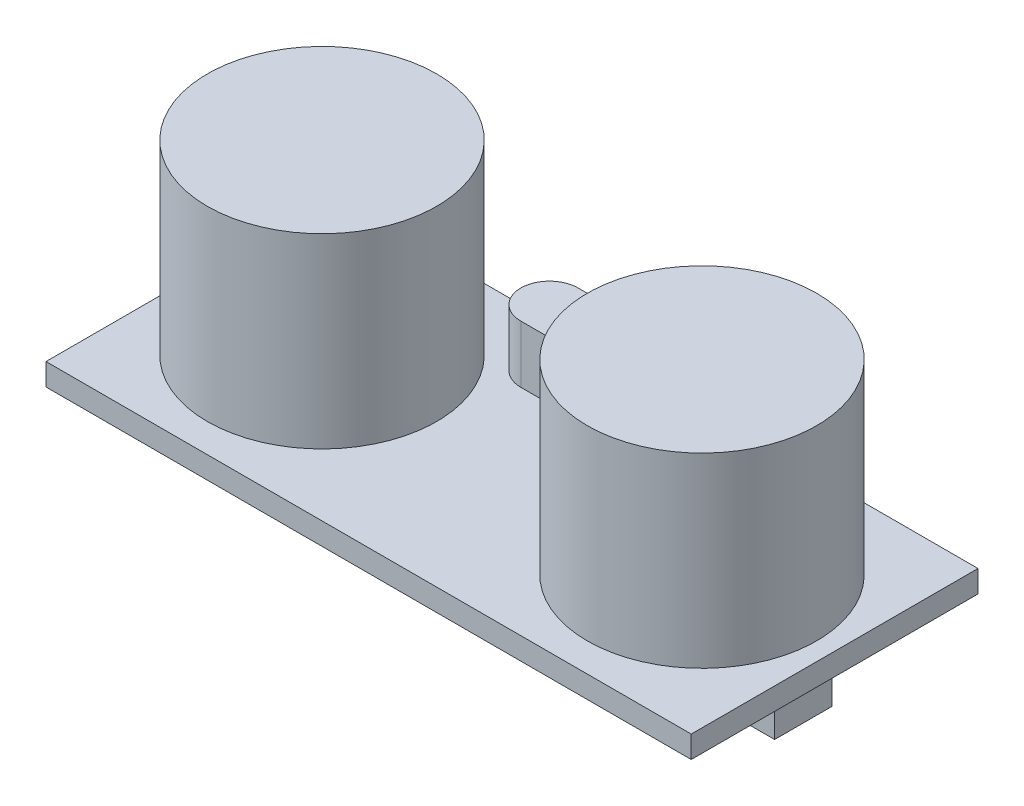
SolidWorks part; units mm, degrees
ref_plane "Front Plane" through (0, 0, 0) normal (0, 0, 1) x (1, 0, 0)
ref_plane "Top Plane" through (0, 0, 0) normal (0, 1, 0) x (1, 0, 0)
ref_plane "Right Plane" through (0, 0, 0) normal (1, 0, 0) x (0, 0, -1)
sketch "Sketch1" plane through (0, 0, 0) normal (0, 1, 0) x (1, 0, 0)
  line L1 (-22.5, -10) -> (22.5, -10)
  line L2 (-22.5, -10) -> (-22.5, 10)
  line L3 (-22.5, 10) -> (22.5, 10)
  line L4 (22.5, -10) -> (22.5, 10)
  line L5 (-22.5, -10) -> (22.5, 10) construction
  line L6 (-22.5, 10) -> (22.5, -10) construction
  point P0 (0, 0)
  dimension "D1" = 45
  dimension "D2" = 20
extrude "Boss-Extrude1" add sketch "Sketch1" along normal blind 1.54
sketch "Sketch2" plane through (0, 1.54, 0) normal (0, 1, 0) x (1, 0, 0)
  line L0 (-22.5, 10) -> (-22.5, -10) construction
  circle A0 centre (-13.25, 0) radius 8
  circle A1 centre (13.25, 0) radius 8
  dimension "D1" = 16
  dimension "D2" = 16
  dimension "D3" = 26.5
  dimension "D4" = 9.25
extrude "Boss-Extrude2" add sketch "Sketch2" along normal blind 13
sketch "Sketch3" plane through (0, 1.54, 0) normal (0, 1, 0) x (1, 0, 0)
  line L0 (-4.3865, 7) -> (4.3865, 7) construction
  line L1 (-4.3865, 9) -> (4.3865, 9)
  line L2 (-4.3865, 5) -> (4.3865, 5)
  line L3 (22.5, 10) -> (-22.5, 10) construction
  arc A0 (-4.3865, 9) -> (-4.3865, 5) centre (-4.3865, 7) ccw
  arc A1 (4.3865, 5) -> (4.3865, 9) centre (4.3865, 7) ccw
  point P2 (0, 7)
  dimension "D1" = 3
  dimension "D2" = 4
extrude "Boss-Extrude3" add sketch "Sketch3" along normal blind 4
sketch "Sketch4" plane through (0, 0, 0) normal (0, 1, 0) x (1, 0, 0)
  line L0 (-22.5, -10) -> (22.5, -10) construction
  line L1 (-4.45, 2) -> (4.45, 2)
  line L2 (-4.45, 2) -> (-4.45, -2)
  line L3 (-4.45, -2) -> (4.45, -2)
  line L4 (4.45, 2) -> (4.45, -2)
  line L5 (-4.45, 2) -> (4.45, -2) construction
  line L6 (-4.45, -2) -> (4.45, 2) construction
  line L7 (11.8, 1.6158) -> (20.7, 1.6158)
  line L8 (11.8, 1.6158) -> (11.8, -2.3842)
  line L9 (11.8, -2.3842) -> (20.7, -2.3842)
  line L10 (20.7, 1.6158) -> (20.7, -2.3842)
  line L11 (11.8, 1.6158) -> (20.7, -2.3842) construction
  line L12 (11.8, -2.3842) -> (20.7, 1.6158) construction
  line L13 (-19.9, -6) -> (-15.9, -6)
  line L14 (-19.9, -6) -> (-19.9, 2.9)
  line L15 (-19.9, 2.9) -> (-15.9, 2.9)
  line L16 (-15.9, -6) -> (-15.9, 2.9)
  line L17 (-19.9, -6) -> (-15.9, 2.9) construction
  line L18 (-19.9, 2.9) -> (-15.9, -6) construction
  line L19 (-22.5, 10) -> (-22.5, -10) construction
  point P0 (0, 0)
  point P6 (16.25, -0.3842)
  point P11 (-17.9, -1.55)
  dimension "D1" = 4
  dimension "D2" = 8.9
  dimension "D3" = 4
  dimension "D4" = 8.9
  dimension "D5" = 20.7
  dimension "D6" = 8.9
  dimension "D7" = 4
  dimension "D8" = 4
  dimension "D9" = 2.6
extrude "Boss-Extrude4" add sketch "Sketch4" against normal blind 3.5
